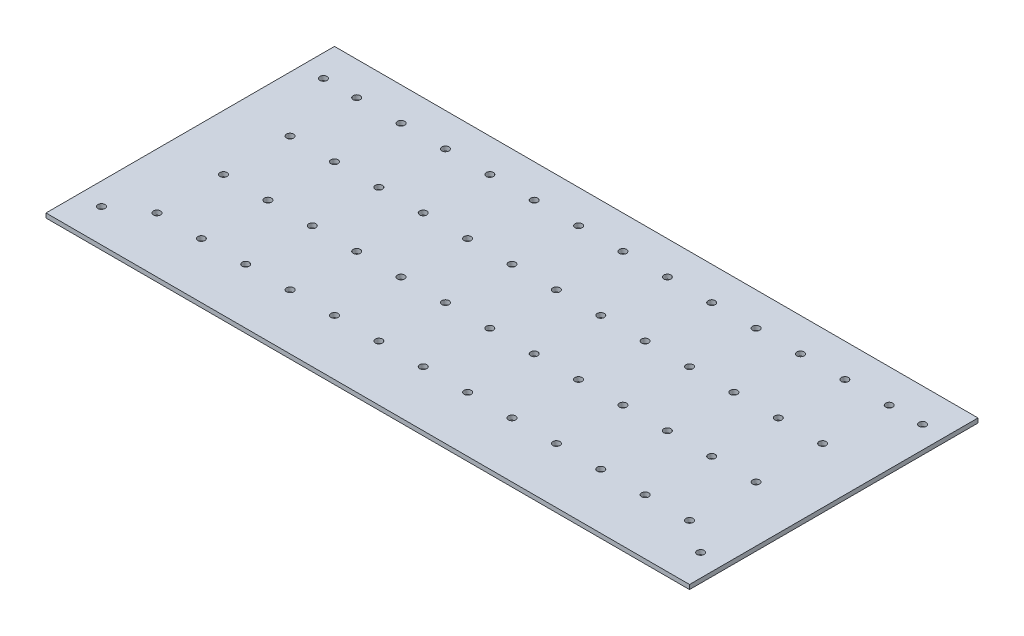
SolidWorks part; units mm, degrees
ref_plane "Front Plane" through (0, 0, 0) normal (0, 0, 1) x (1, 0, 0)
ref_plane "Top Plane" through (0, 0, 0) normal (0, 1, 0) x (1, 0, 0)
ref_plane "Right Plane" through (0, 0, 0) normal (1, 0, 0) x (0, 0, -1)
sketch "Sketch1" plane through (0, 0, 0) normal (0, 1, 0) x (1, 0, 0)
  line L0 (0, -55) -> (0, 55) construction
  line L1 (-145, -65) -> (145, -65)
  line L2 (-145, -65) -> (-145, 65)
  line L3 (-145, 65) -> (145, 65)
  line L4 (145, -65) -> (145, 65)
  line L5 (-145, -65) -> (145, 65) construction
  line L6 (-145, 65) -> (145, -65) construction
  line L7 (-135, 50) -> (135, 50) construction
  line L8 (-135, 50) -> (-135, -50) construction
  line L9 (-135, -50) -> (135, -50) construction
  line L10 (135, 50) -> (135, -50) construction
  line L11 (-55, 0) -> (55, 0) construction
  circle A0 centre (-135, 50) radius 1.6
  circle A1 centre (-135, -50) radius 1.6
  circle A2 centre (135, -50) radius 1.6
  circle A3 centre (135, 50) radius 1.6
  circle A4 centre (-120, 50) radius 1.6
  circle A5 centre (-100, 50) radius 1.6
  circle A6 centre (-80, 50) radius 1.6
  circle A7 centre (-60, 50) radius 1.6
  circle A8 centre (-40, 50) radius 1.6
  circle A9 centre (-20, 50) radius 1.6
  circle A10 centre (0, 50) radius 1.6
  circle A11 centre (20, 50) radius 1.6
  circle A12 centre (40, 50) radius 1.6
  circle A13 centre (60, 50) radius 1.6
  circle A14 centre (80, 50) radius 1.6
  circle A15 centre (100, 50) radius 1.6
  circle A16 centre (120, 50) radius 1.6
  circle A17 centre (-100, 20) radius 1.6
  circle A18 centre (-80, 20) radius 1.6
  circle A19 centre (-60, 20) radius 1.6
  circle A20 centre (-40, 20) radius 1.6
  circle A21 centre (-20, 20) radius 1.6
  circle A22 centre (0, 20) radius 1.6
  circle A23 centre (20, 20) radius 1.6
  circle A24 centre (40, 20) radius 1.6
  circle A25 centre (60, 20) radius 1.6
  circle A26 centre (80, 20) radius 1.6
  circle A27 centre (100, 20) radius 1.6
  circle A28 centre (120, 20) radius 1.6
  circle A29 centre (-100, -10) radius 1.6
  circle A30 centre (-80, -10) radius 1.6
  circle A31 centre (-60, -10) radius 1.6
  circle A32 centre (-40, -10) radius 1.6
  circle A33 centre (-20, -10) radius 1.6
  circle A34 centre (0, -10) radius 1.6
  circle A35 centre (20, -10) radius 1.6
  circle A36 centre (40, -10) radius 1.6
  circle A37 centre (60, -10) radius 1.6
  circle A38 centre (80, -10) radius 1.6
  circle A39 centre (100, -10) radius 1.6
  circle A40 centre (120, -10) radius 1.6
  circle A41 centre (-100, -40) radius 1.6
  circle A42 centre (-80, -40) radius 1.6
  circle A43 centre (-60, -40) radius 1.6
  circle A44 centre (-40, -40) radius 1.6
  circle A45 centre (-20, -40) radius 1.6
  circle A46 centre (0, -40) radius 1.6
  circle A47 centre (20, -40) radius 1.6
  circle A48 centre (40, -40) radius 1.6
  circle A49 centre (60, -40) radius 1.6
  circle A50 centre (80, -40) radius 1.6
  circle A51 centre (100, -40) radius 1.6
  circle A52 centre (120, -40) radius 1.6
  circle A53 centre (-120, 20) radius 1.6
  circle A54 centre (-120, -10) radius 1.6
  circle A55 centre (-120, -40) radius 1.6
  point P0 (0, 0)
  point P8 (-120, 50)
  point P19 (0, 50)
  point P22 (-135, 0)
  dimension "D3" = 3.2
  dimension "D6" = 15
  dimension "D1" = 130
  dimension "D2" = 290
  dimension "D4" = 10
  dimension "D5" = 100
  dimension "D7" = 13
  dimension "D8" = 4
extrude "Boss-Extrude1" add sketch "Sketch1" along normal blind 2
